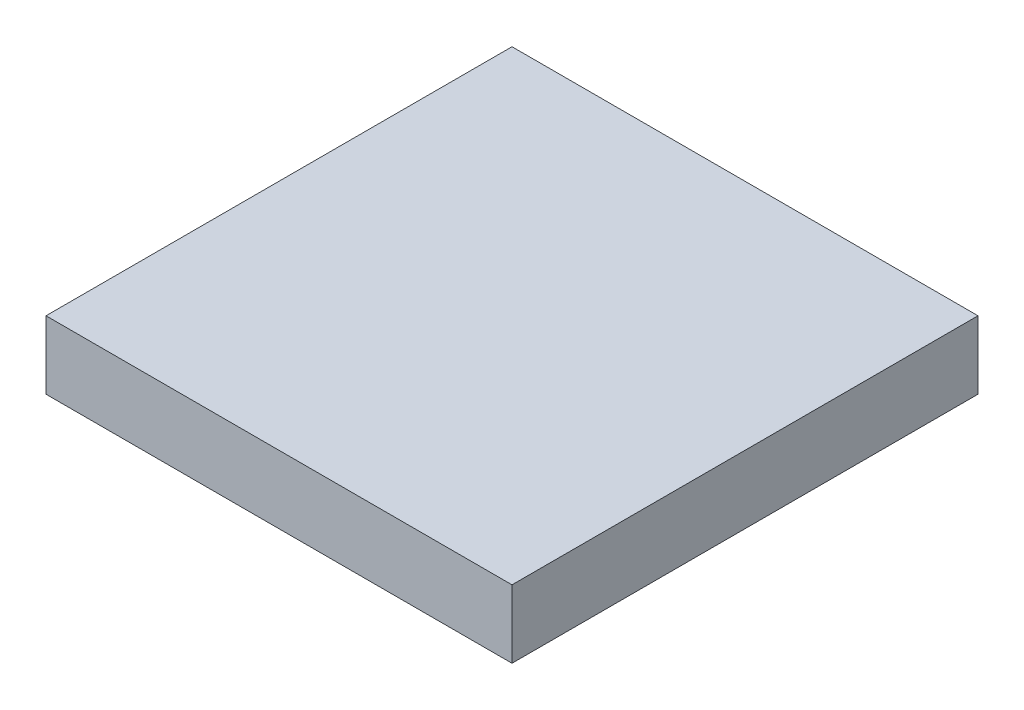
SolidWorks part; units mm, degrees
ref_plane "Front Plane" through (0, 0, 0) normal (0, 0, 1) x (1, 0, 0)
ref_plane "Top Plane" through (0, 0, 0) normal (0, 1, 0) x (1, 0, 0)
ref_plane "Right Plane" through (0, 0, 0) normal (1, 0, 0) x (0, 0, -1)
sketch "Sketch1" plane through (0, 0, 0) normal (0, 0, 1) x (1, 0, 0)
  line L7 (-76.2, -11.1125) -> (76.2, -11.1125)
  line L8 (-76.2, -11.1125) -> (-76.2, 11.1125)
  line L9 (-76.2, 11.1125) -> (76.2, 11.1125)
  line L10 (76.2, -11.1125) -> (76.2, 11.1125)
  line L11 (-76.2, -11.1125) -> (76.2, 11.1125) construction
  line L12 (-76.2, 11.1125) -> (76.2, -11.1125) construction
  point P4 (0, 0)
  point P14 (0, 0)
  dimension "Thickness" = 22.225
  dimension "Width" = 152.4
sketch "Sketch2" plane through (0, 0, 0) normal (0, 1, 0) x (0, 0, -1)
  line L0 (76.2, 76.2) -> (-76.2, 76.2) construction
  point P4 (0, 76.2)
  dimension "Length" = 152.4
sketch "Sketch3" plane through (0, 0, 0) normal (0, 0, 1) x (1, 0, 0)
  line L6 (-76.2, 11.1125) -> (76.2, 11.1125)
  line L7 (76.2, 11.1125) -> (76.2, -11.1125)
  line L8 (76.2, -11.1125) -> (-76.2, -11.1125)
  line L9 (-76.2, -11.1125) -> (-76.2, 11.1125)
extrude "Boss-Extrude1" add sketch "Sketch3" along normal mid plane 152.4
equation "\"D1@Boss-Extrude1\" = \"Length@Sketch2\""
